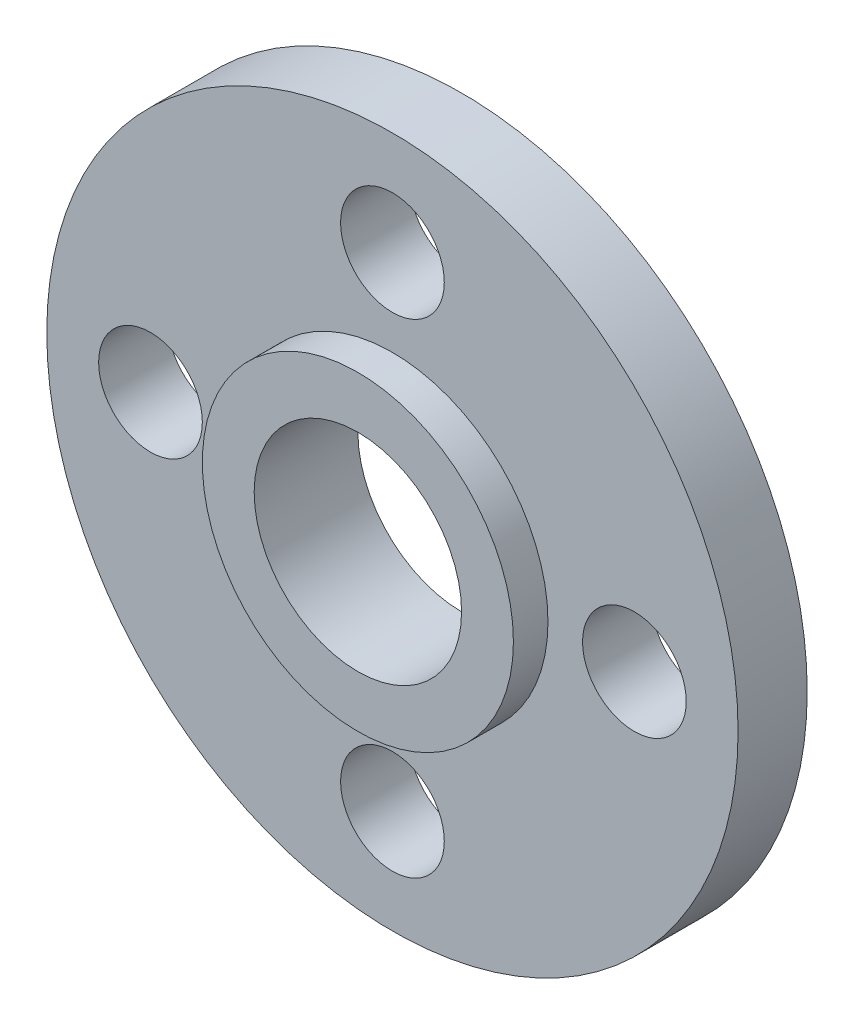
SolidWorks part; units mm, degrees
ref_plane "Спереди" through (0, 0, 0) normal (0, 0, 1) x (1, 0, 0)
ref_plane "Сверху" through (0, 0, 0) normal (0, 1, 0) x (1, 0, 0)
ref_plane "Справа" through (0, 0, 0) normal (1, 0, 0) x (0, 0, -1)
sketch "Sketch1" plane through (0, 0, 0) normal (0, 0, 1) x (1, 0, 0)
  circle A0 centre (0, 0) radius 10
extrude "Extrude1" add sketch "Sketch1" along normal blind 2.5
sketch "Sketch2" plane through (0, 0, 2.5) normal (0, 0, 1) x (1, 0, 0)
  circle A0 centre (0, 0) radius 4.5
  circle A1 centre (0, 0) radius 3
extrude "Extrude2" add sketch "Sketch2" along normal blind 2
sketch "Sketch3" plane through (0, 0, 2.5) normal (0, 0, 1) x (1, 0, 0)
  circle A0 centre (0, 0) radius 1.5
extrude "Extrude3" cut sketch "Sketch3" against normal blind 13
sketch "Sketch4" plane through (0, 0, 2.5) normal (0, 0, 1) x (1, 0, 0)
  circle A2 centre (0, 7.25) radius 1.5
  circle A3 centre (7.25, 0) radius 1.5
  circle A4 centre (0, -7.25) radius 1.5
  circle A5 centre (-7.25, 0) radius 1.5
  point P12 (0, 0)
  dimension "D1" = 4
extrude "Extrude4" cut sketch "Sketch4" against normal blind 13
sketch "Sketch5" plane through (0, 0, 2.5) normal (0, 0, 1) x (1, 0, 0)
  circle A0 centre (0, 0) radius 3
extrude "Extrude5" cut sketch "Sketch5" against normal blind 13
sketch "Sketch6" plane through (0, 0, 4.5) normal (0, 0, 1) x (1, 0, 0)
  circle A0 centre (0, 0) radius 4.5
extrude "Extrude6" cut sketch "Sketch6" against normal blind 1
sketch "Sketch7" plane through (0, 0, 2.5) normal (0, 0, 1) x (1, 0, 0)
  circle A0 centre (0, 0) radius 10
  circle A1 centre (0, 0) radius 4.5
extrude "Extrude7" cut sketch "Sketch7" against normal blind 0.5
sketch "Sketch8" plane through (0, 0, 3.5) normal (0, 0, 1) x (1, 0, 0)
  circle A0 centre (0, 0) radius 4.5
extrude "Extrude8" cut sketch "Sketch8" against normal blind 0.5
sketch "Sketch9" plane through (0, 0, 0) normal (0, 0, -1) x (-1, 0, 0)
  circle A0 centre (0, 0) radius 3
  circle A1 centre (0, 0) radius 10
extrude "Extrude9" add sketch "Sketch9" against normal blind 2
sketch "Sketch10" plane through (0, 0, 0) normal (0, 0, -1) x (-1, 0, 0)
  circle A1 centre (0, 7) radius 1.5
  circle A2 centre (7, 0) radius 1.5
  circle A3 centre (0, -7) radius 1.5
  circle A4 centre (-7, 0) radius 1.5
  point P13 (0, 0)
  dimension "D1" = 4
extrude "Extrude10" cut sketch "Sketch10" against normal blind 12.3
